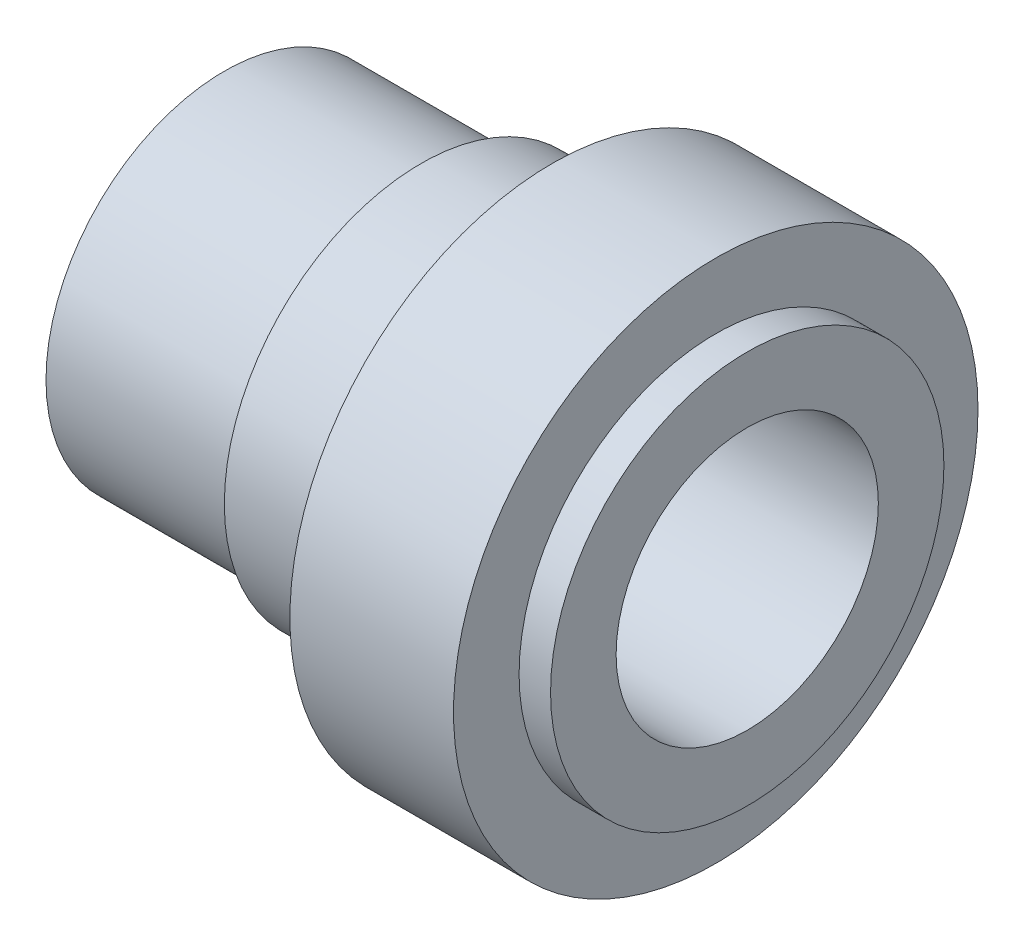
SolidWorks part; units mm, degrees
ref_plane "Front Plane" through (0, 0, 0) normal (0, 0, 1) x (1, 0, 0)
ref_plane "Top Plane" through (0, 0, 0) normal (0, 1, 0) x (1, 0, 0)
ref_plane "Right Plane" through (0, 0, 0) normal (1, 0, 0) x (0, 0, -1)
sketch "Sketch1" plane through (0, 0, 0) normal (1, 0, 0) x (0, 0, -1)
  circle A0 centre (0, 0) radius 12.7
  dimension "D1" = 25.4
extrude "Boss-Extrude1" add sketch "Sketch1" along normal blind 7.9248
sketch "Sketch2" plane through (7.9248, 0, 0) normal (1, 0, 0) x (0, 0, -1)
  circle A0 centre (0, 0) radius 9.525
  dimension "D1" = 19.05
extrude "Boss-Extrude2" add sketch "Sketch2" along normal blind 1.524
sketch "Sketch4" plane through (0, 0, 0) normal (-1, 0, 0) x (0, 0, 1)
  circle A0 centre (0, 0) radius 9.525
  dimension "D1" = 19.05
extrude "Boss-Extrude4" add sketch "Sketch4" along normal blind 6.35
sketch "Sketch5" plane through (-6.35, 0, 0) normal (-1, 0, 0) x (0, 0, 1)
  circle A0 centre (0, 0) radius 8.636
  dimension "D1" = 17.272
extrude "Boss-Extrude5" add sketch "Sketch5" along normal blind 9.525
sketch "Sketch6" plane through (-15.875, 0, 0) normal (-1, 0, 0) x (0, 0, 1)
  circle A0 centre (0, 0) radius 6.35
  dimension "D1" = 12.7
extrude "Cut-Extrude1" cut sketch "Sketch6" against normal blind 25.4
